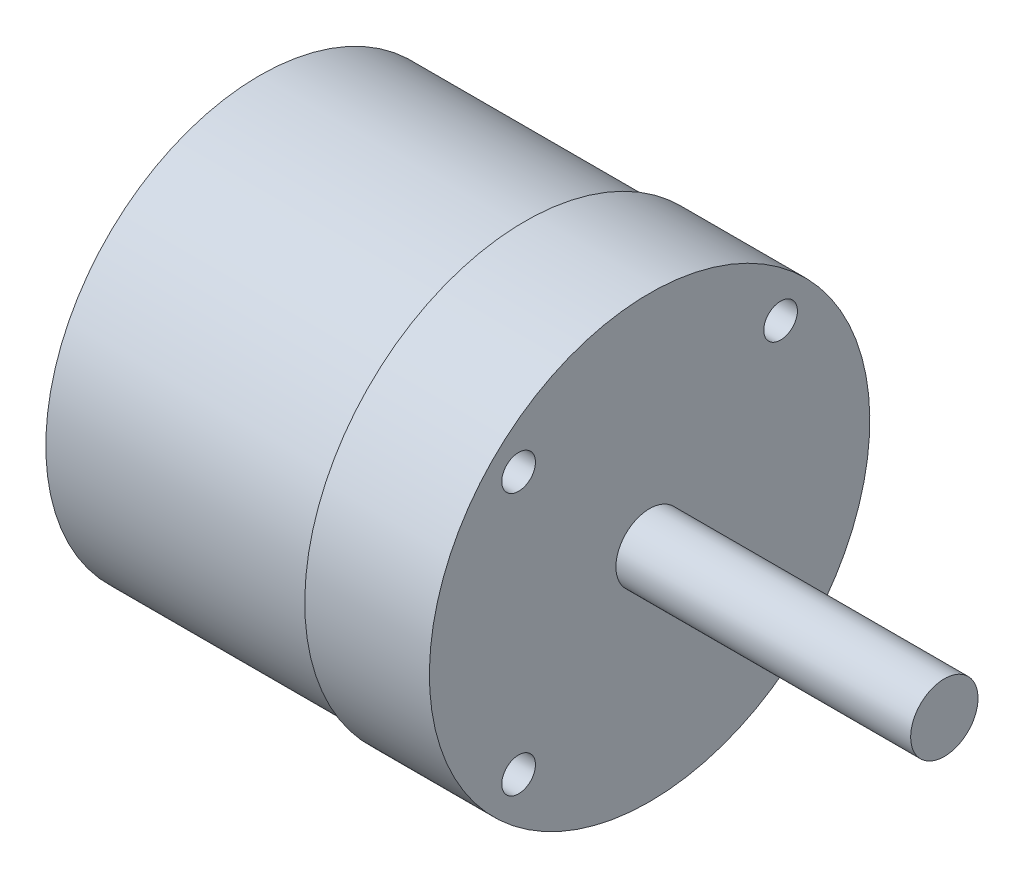
SolidWorks part; units mm, degrees
ref_plane "Top Plane" through (0, 0, 0) normal (0, 0, 1) x (1, 0, 0)
ref_plane "Front Plane" through (0, 0, 0) normal (0, 1, 0) x (1, 0, 0)
ref_plane "Right Plane" through (0, 0, 0) normal (1, 0, 0) x (0, 0, -1)
sketch "Sketch2" plane through (0, 0, 0) normal (0, 0, 1) x (1, 0, 0)
  line L0 (-163.9254, 0) -> (163.9254, 0) construction
  line L1 (-54.3, 0) -> (-54.3, 5)
  line L2 (-54.3, 5) -> (-52.3, 5)
  line L3 (-52.3, 5) -> (-52.3, 7.5)
  line L4 (-52.3, 7.5) -> (-46.3, 7.5)
  line L5 (-46.3, 7.5) -> (-46.3, 25.4)
  line L6 (-46.3, 25.4) -> (-14.8, 25.4)
  line L7 (-14.8, 25.4) -> (-14.8, 26.15)
  line L8 (-14.8, 26.15) -> (0, 26.15)
  line L9 (0, 26.15) -> (0, 4)
  line L10 (0, 4) -> (35, 4)
  line L11 (35, 4) -> (35, 0)
  line L12 (-54.3, 0) -> (35, 0)
  point P2 (0, 0)
  dimension "D1" = 26.15
  dimension "D2" = 25.4
  dimension "D3" = 7.5
  dimension "D4" = 5
  dimension "D5" = 2
  dimension "D6" = 6
  dimension "D7" = 31.5
  dimension "D8" = 14.8
  dimension "D9" = 35
  dimension "D10" = 4
revolve "Revolve1" add sketch "Sketch2" angle 360 about L0
sketch "Sketch3" plane through (0, 0, 0) normal (1, 0, 0) x (0, 0, -1)
  line L0 (-15.5563, -15.5563) -> (15.5563, 15.5563) construction
  line L1 (-15.5563, -15.5563) -> (15.5563, -15.5563) construction
  line L2 (-15.5563, -15.5563) -> (-15.5563, 15.5563) construction
  line L3 (-15.5563, 15.5563) -> (15.5563, 15.5563) construction
  line L4 (15.5563, -15.5563) -> (15.5563, 15.5563) construction
  circle A0 centre (-15.5563, -15.5563) radius 2
  circle A1 centre (-15.5563, 15.5563) radius 2
  circle A2 centre (15.5563, 15.5563) radius 2
  circle A3 centre (15.5563, -15.5563) radius 2
  point P4 (0, 0)
  dimension "D1" = 4
  dimension "D2" = 44
extrude "Cut-Extrude1" cut sketch "Sketch3" against normal blind 10
ref_plane "Plane2" through (0, -4, 0) normal (0, -1, 0) x (-1, 0, 0)
sketch "Sketch5" plane through (0, -4, 0) normal (0, -1, 0) x (-1, 0, 0)
  line L0 (-12.5, 0) -> (-17.5, 0) construction
  line L1 (-12.5, -1.5) -> (-17.5, -1.5)
  line L2 (-12.5, 1.5) -> (-17.5, 1.5)
  line L3 (0, 0) -> (-12.5, 0) construction
  arc A0 (-12.5, -1.5) -> (-12.5, 1.5) centre (-12.5, 0) ccw
  arc A1 (-17.5, 1.5) -> (-17.5, -1.5) centre (-17.5, 0) ccw
  point P2 (-15, 0)
  dimension "D1" = 1.5
  dimension "D3" = 8
  dimension "D2" = 11
extrude "Cut-Extrude2" cut sketch "Sketch5" against normal blind 2
ref_plane "Plane1" through (0, 0, 0) normal (0, 0, 1) x (1, 0, 0)
